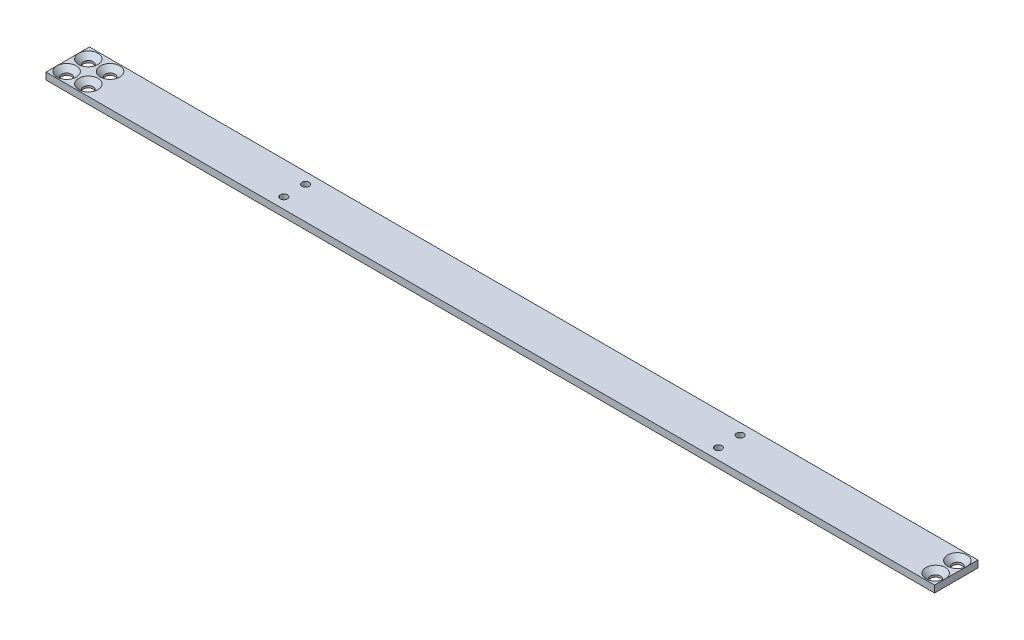
SolidWorks part; units mm, degrees
ref_plane "Front Plane" through (0, 0, 0) normal (0, 0, 1) x (1, 0, 0)
ref_plane "Top Plane" through (0, 0, 0) normal (0, 1, 0) x (1, 0, 0)
ref_plane "Right Plane" through (0, 0, 0) normal (1, 0, 0) x (0, 0, -1)
sketch "Sketch1" plane through (0, 0, 0) normal (0, 1, 0) x (1, 0, 0)
  line L1 (-204.5, -10) -> (204.5, -10)
  line L2 (-204.5, -10) -> (-204.5, 10)
  line L3 (-204.5, 10) -> (204.5, 10)
  line L4 (204.5, -10) -> (204.5, 10)
  line L5 (-204.5, -10) -> (204.5, 10) construction
  line L6 (-204.5, 10) -> (204.5, -10) construction
  point P0 (0, 0)
  dimension "D1" = 409
  dimension "D2" = 20
extrude "Boss-Extrude1" add sketch "Sketch1" along normal blind 3.175
hole_wizard "CSK for M4 SFHCS1" positions "Sketch2" profile "Sketch4" countersink size "M4" standard "ANSI Metric" end condition through all
sketch "Sketch2" plane through (0, 3.175, 0) normal (0, 1, 0) x (1, 0, 0)
  line L1 (-200, -5) -> (-190, -5)
  line L2 (-200, -5) -> (-200, 5)
  line L3 (-200, 5) -> (-190, 5)
  line L4 (-190, -5) -> (-190, 5)
  line L5 (-200, -5) -> (-190, 5) construction
  line L6 (-200, 5) -> (-190, -5) construction
  line L7 (-204.5, 10) -> (-204.5, -10) construction
  line L8 (200, 5) -> (200, -5)
  line L10 (204.5, -10) -> (204.5, 10) construction
  point P2 (-190, 5)
  point P61 (-200, -5)
  point P62 (-200, 5)
  point P63 (-190, -5)
  point P67 (-195, 0)
  point P69 (200, 5)
  point P70 (200, -5)
  point P75 (200, 0)
  dimension "D1" = 10
  dimension "D2" = 4.5
  dimension "D3" = 10
  dimension "D4" = 4.5
sketch "Sketch4" plane through (-190, 3.175, -5) normal (1, 0, 0) x (0, 0, 1)
  line L0 (0, 0) -> (0, 3.175)
  line L1 (0, 3.175) -> (2.25, 3.175)
  line L2 (2.25, 3.175) -> (2.25, 2.23)
  line L3 (2.25, 2.23) -> (4.48, 0)
  line L5 (4.48, 0) -> (0, 0)
  line L6 (-2.25, 2.23) -> (-4.48, 0) construction
  line L11 (0, -6.35) -> (0, 107.95) construction
  dimension "Thru Hole Dia." = 4.5
  dimension "Thru Hole Depth" = 3.175
  dimension "Near C'Sink Dia." = 8.96
  dimension "Near C'Sink Angle" = 90
hole_wizard "M4x0.7 Tapped Hole1" positions "Sketch5" profile "Sketch7" tap size "M4x0.7" standard "ANSI Metric" end condition through all
sketch "Sketch5" plane through (0, 3.175, 0) normal (0, 1, 0) x (1, 0, 0)
  line L1 (-100, -5) -> (100, -5)
  line L2 (-100, -5) -> (-100, 5)
  line L3 (-100, 5) -> (100, 5)
  line L4 (100, -5) -> (100, 5)
  line L5 (-100, -5) -> (100, 5) construction
  line L6 (-100, 5) -> (100, -5) construction
  point P2 (100, 5)
  point P45 (-100, -5)
  point P46 (-100, 5)
  point P47 (100, -5)
  point P52 (0, 0)
  dimension "D1" = 10
  dimension "D2" = 200
sketch "Sketch7" plane through (100, 3.175, -5) normal (1, 0, 0) x (0, 0, 1)
  line L0 (0, 0) -> (0, 3.175)
  line L1 (0, 3.175) -> (1.65, 3.175)
  line L2 (1.65, 3.175) -> (1.65, 0)
  line L5 (1.65, 0) -> (0, 0)
  line L11 (0, -6.35) -> (0, 107.95) construction
  dimension "Thru Tap Drill Dia." = 3.3
  dimension "Thru Tap Drill Depth" = 3.175
cosmetic thread "Hole Thread1" parameters "D2"=4
cosmetic thread "Hole Thread2" parameters "D2"=4
cosmetic thread "Hole Thread3" parameters "D2"=4
cosmetic thread "Hole Thread4" parameters "D2"=4
